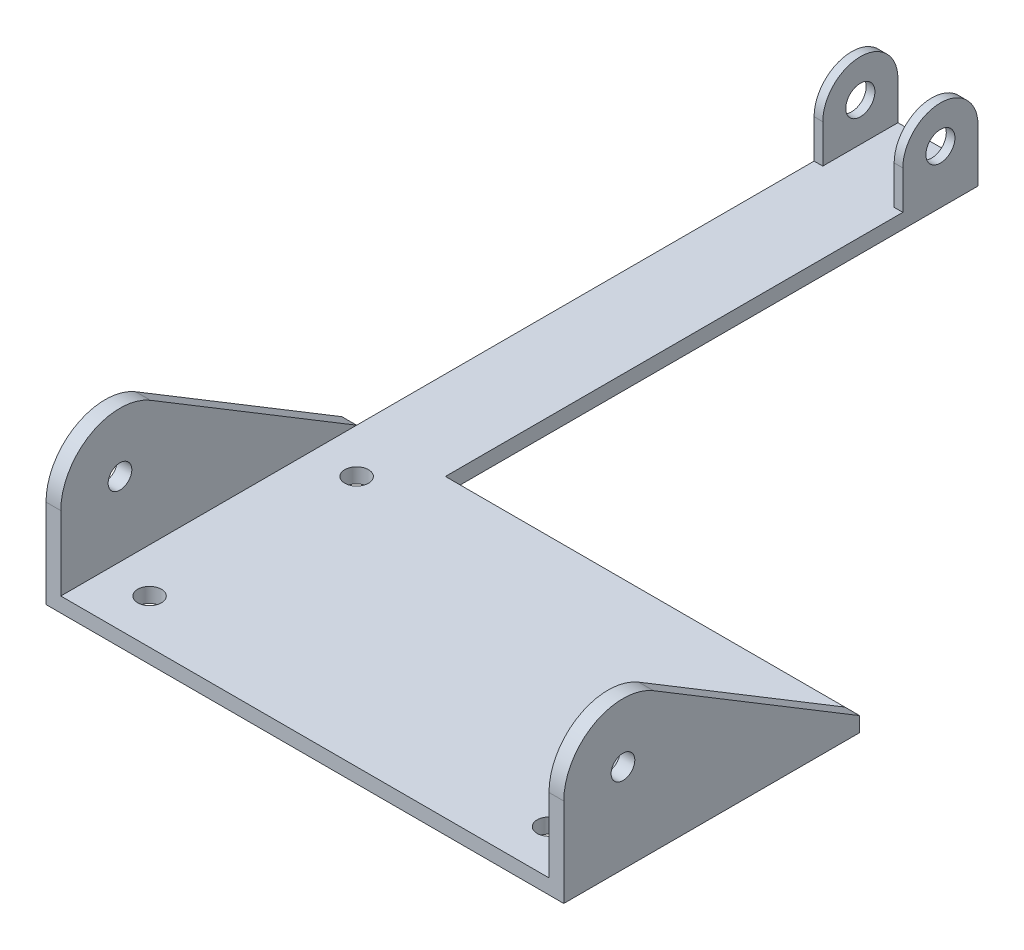
SolidWorks part; units mm, degrees
ref_plane "Front Plane" through (0, 0, 0) normal (0, 0, 1) x (1, 0, 0)
ref_plane "Top Plane" through (0, 0, 0) normal (0, 1, 0) x (1, 0, 0)
ref_plane "Right Plane" through (0, 0, 0) normal (1, 0, 0) x (0, 0, -1)
sketch "Sketch1" plane through (0, 0, 0) normal (0, 0, 1) x (1, 0, 0)
  line L0 (0, 50) -> (5, 50)
  line L1 (5, 50) -> (5, 5)
  line L2 (5, 5) -> (170, 5)
  line L3 (170, 5) -> (170, 50)
  line L4 (170, 50) -> (175, 50)
  line L5 (175, 50) -> (175, 0)
  line L6 (175, 0) -> (0, 0)
  line L7 (0, 0) -> (0, 50)
  point P4 (0, 0)
  dimension "D1" = 165
  dimension "D2" = 5
  dimension "D3" = 5
  dimension "D4" = 5
  dimension "D5" = 45
  dimension "D6" = 45
extrude "Boss-Extrude1" add sketch "Sketch1" along normal blind 100
sketch "Sketch2" plane through (0, 0, 0) normal (-1, 0, 0) x (0, 0, 1)
  line L0 (0, 5) -> (100, 5) construction
  line L1 (0, 50) -> (0, 0) construction
  line L2 (100, 50) -> (100, 0) construction
  line L3 (100, 0) -> (0, 0) construction
  line L4 (100, 50) -> (0, 50) construction
  line L5 (100, 30) -> (100, 5)
  line L6 (100, 5) -> (131.664, 33.6972)
  line L7 (0, 5) -> (69.6517, 47.1147)
  line L8 (131.664, 33.6972) -> (100, 64.7419)
  line L9 (100, 64.7419) -> (-14.7909, 55.9261)
  line L10 (-14.7909, 55.9261) -> (0, 5)
  circle A0 centre (80, 30) radius 20 construction
  circle A1 centre (80, 30) radius 4
  arc A2 (100, 30) -> (69.6517, 47.1147) centre (80, 30) ccw
  dimension "D2" = 40
  dimension "D3" = 8
  dimension "D1" = 5
extrude "Cut-Extrude1" cut sketch "Sketch2" against normal through all
sketch "Sketch3" plane through (0, 5, 0) normal (0, 1, 0) x (1, 0, 0)
  line L0 (170, -100) -> (170, 0) construction
  line L1 (20, -15) -> (155, -15) construction
  line L2 (20, -15) -> (20, -85) construction
  line L3 (20, -85) -> (155, -85) construction
  line L4 (155, -15) -> (155, -85) construction
  line L5 (5, -100) -> (5, 0) construction
  line L6 (170, 0) -> (5, 0) construction
  line L7 (170, -100) -> (5, -100) construction
  circle A0 centre (20, -15) radius 4
  circle A1 centre (155, -15) radius 4
  circle A2 centre (155, -85) radius 4
  circle A3 centre (20, -85) radius 4
  dimension "D5" = 8
  dimension "D6" = 8
  dimension "D7" = 8
  dimension "D8" = 8
  dimension "D1" = 15
  dimension "D2" = 15
  dimension "D3" = 15
  dimension "D4" = 15
extrude "Cut-Extrude2" cut sketch "Sketch3" against normal through all
sketch "Sketch4" plane through (0, 5, 0) normal (0, 1, 0) x (1, 0, 0)
  line L1 (5, 0) -> (35, 0)
  line L2 (5, 0) -> (5, 180)
  line L3 (5, 180) -> (35, 180)
  line L4 (35, 0) -> (35, 180)
  dimension "D1" = 30
  dimension "D2" = 180
extrude "Boss-Extrude2" add sketch "Sketch4" against normal up to surface (5 mm away) contours L2 L3 L4 L1 up to face at (20, 0, 89)
sketch "Sketch5" plane through (5, 0, 0) normal (-1, 0, 0) x (0, 0, 1)
  line L1 (-180, 5) -> (-154.6, 5)
  line L2 (-180, 5) -> (-180, 18)
  line L4 (-154.6, 5) -> (-154.6, 18)
  arc A0 (-180, 18) -> (-154.6, 18) centre (-167.3, 18) cw
  circle A1 centre (-167.3, 18) radius 4.915
  line M4 (0, 5) -> (-180, 5)
  dimension "D3" = 9.83
  dimension "D1" = 25.4
  dimension "D2" = 13
extrude "Boss-Extrude3" add sketch "Sketch5" against normal up to surface (30 mm away) contours A0 L2 L4 A1 M4
sketch "Sketch6" plane through (0, 5, 0) normal (0, 1, 0) x (1, 0, 0)
  line L0 (20, 217.6189) -> (20, 108.1564) construction
  line L1 (7.935, 217.6189) -> (32.065, 217.6189)
  line L2 (7.935, 217.6189) -> (7.935, 108.1564)
  line L3 (7.935, 108.1564) -> (32.065, 108.1564)
  line L4 (32.065, 217.6189) -> (32.065, 108.1564)
  line L5 (35, 180) -> (5, 180) construction
  point P8 (20, 180)
  dimension "D1" = 24.13
extrude "Cut-Extrude3" cut sketch "Sketch6" along normal through all contours L4 L3 L2 L1
